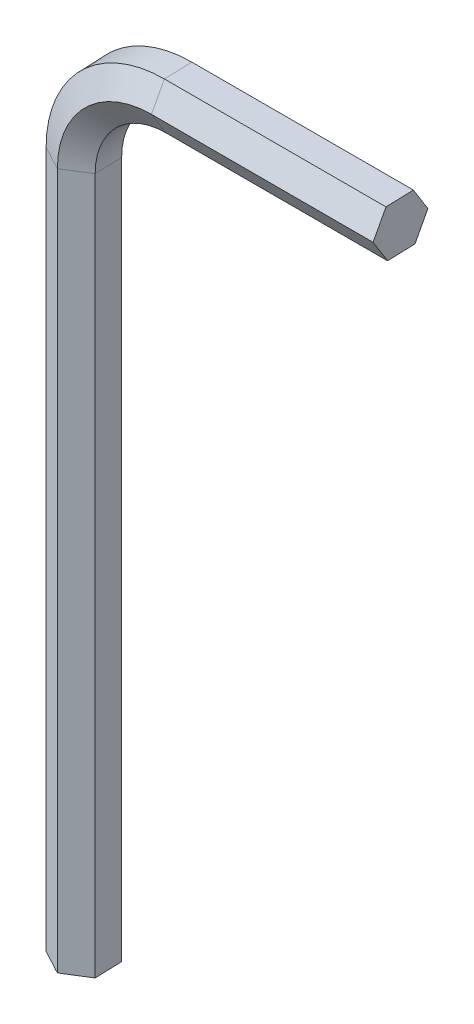
SolidWorks part; units mm, degrees
ref_plane "Front Plane" through (0, 0, 0) normal (0, 0, 1) x (1, 0, 0)
ref_plane "Top Plane" through (0, 0, 0) normal (0, 1, 0) x (1, 0, 0)
ref_plane "Right Plane" through (0, 0, 0) normal (1, 0, 0) x (0, 0, -1)
sketch "Sketch1" plane through (0, 0, 0) normal (0, 0, 1) x (1, 0, 0)
  line L0 (0, 0) -> (0, 55.88)
  line L1 (7.62, 63.5) -> (25.4, 63.5)
  arc A0 (0, 55.88) -> (7.62, 63.5) centre (7.62, 55.88) cw
  point P6 (0, 63.5)
  dimension "D3" = 7.62
  dimension "D1" = 63.5
  dimension "D2" = 25.4
sketch "Sketch2" plane through (0, 0, 0) normal (0, 1, 0) x (1, 0, 0)
  line L1 (1.8677, 1.1621) -> (-0.0726, 2.1985)
  line L2 (-0.0726, 2.1985) -> (-1.9402, 1.0364)
  line L3 (-1.9402, 1.0364) -> (-1.8677, -1.1621)
  line L4 (-1.8677, -1.1621) -> (0.0726, -2.1985)
  line L5 (0.0726, -2.1985) -> (1.9402, -1.0364)
  line L6 (1.9402, -1.0364) -> (1.8677, 1.1621)
  circle A0 centre (0, 0) radius 1.905 construction
  dimension "D1" = 3.81
sweep "Sweep1" add profiles "Sketch2" path "Sketch1"
